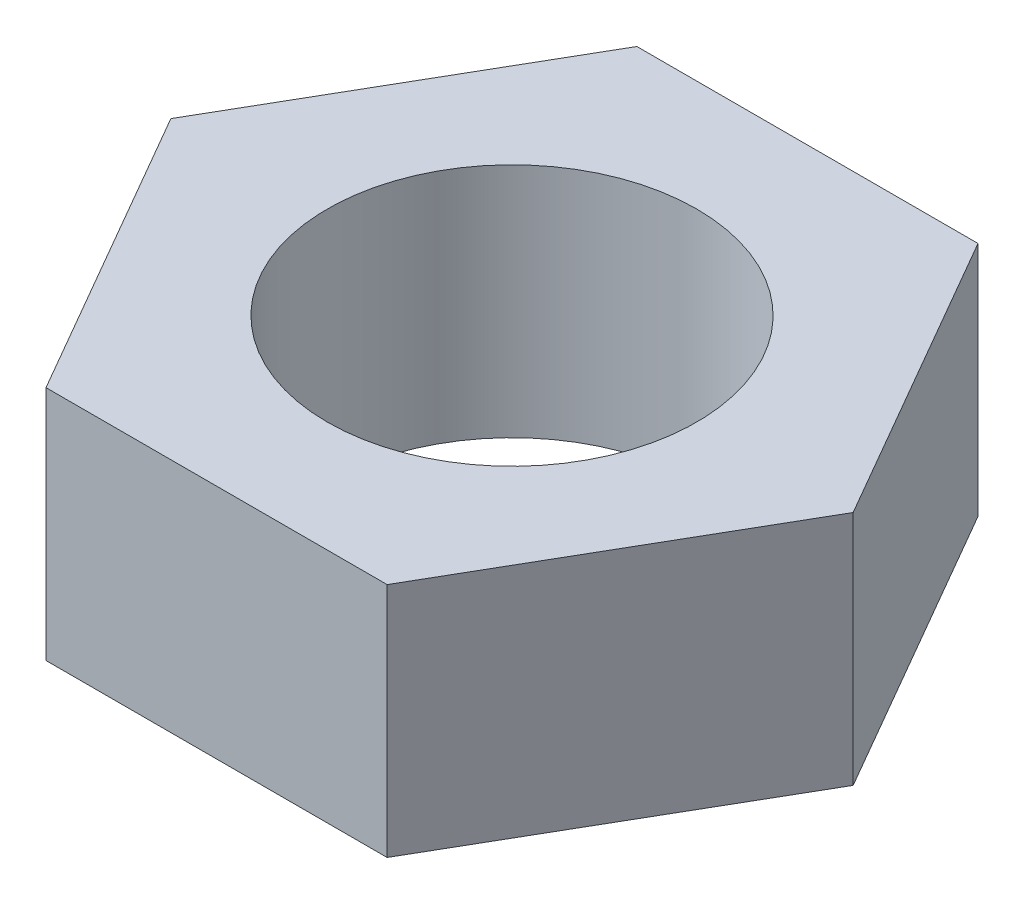
SolidWorks part; units mm, degrees
ref_plane "Спереди" through (0, 0, 0) normal (0, 0, 1) x (1, 0, 0)
ref_plane "Сверху" through (0, 0, 0) normal (0, 1, 0) x (1, 0, 0)
ref_plane "Справа" through (0, 0, 0) normal (1, 0, 0) x (0, 0, -1)
sketch "Эскиз1" plane through (0, 0, 0) normal (0, 1, 0) x (1, 0, 0)
  line L1 (-2.3094, 0) -> (-1.1547, -2)
  line L2 (-1.1547, -2) -> (1.1547, -2)
  line L3 (1.1547, -2) -> (2.3094, 0)
  line L4 (2.3094, 0) -> (1.1547, 2)
  line L5 (1.1547, 2) -> (-1.1547, 2)
  line L6 (-1.1547, 2) -> (-2.3094, 0)
  circle A0 centre (0, 0) radius 2 construction
  dimension "D1" = 4
extrude "Бобышка-Вытянуть1" add sketch "Эскиз1" along normal blind 1.6
sketch "Эскиз2" plane through (0, 1.6, 0) normal (0, 1, 0) x (1, 0, 0)
  circle A0 centre (0, 0) radius 1.25
  dimension "D1" = 2.5
extrude "Вырез-Вытянуть1" cut sketch "Эскиз2" against normal blind 2.4
cosmetic thread "Условное изображение резьбы1" parameters "D2"=3
